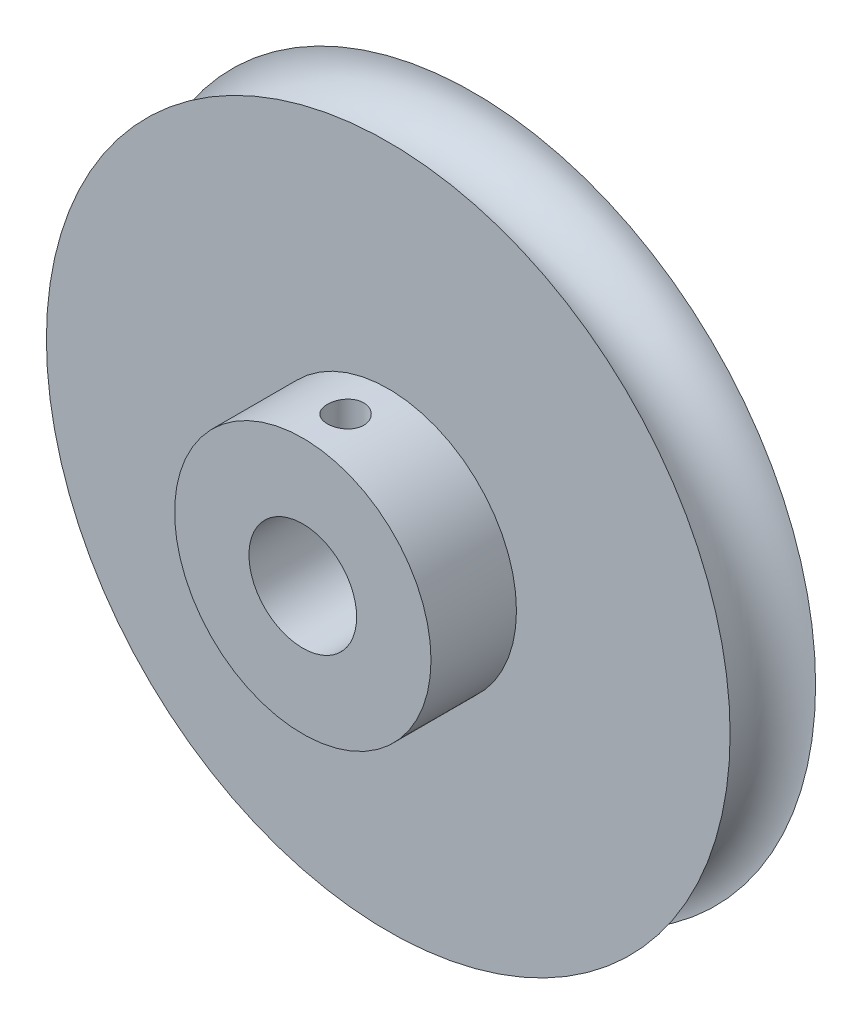
SolidWorks part; units mm, degrees
ref_plane "Front Plane" through (0, 0, 0) normal (0, 0, 1) x (1, 0, 0)
ref_plane "Top Plane" through (0, 0, 0) normal (0, 1, 0) x (1, 0, 0)
ref_plane "Right Plane" through (0, 0, 0) normal (1, 0, 0) x (0, 0, -1)
sketch "Sketch1" plane through (0, 0, 0) normal (0, 0, 1) x (1, 0, 0)
  circle A0 centre (0, 0) radius 25.4
extrude "Boss-Extrude1" add sketch "Sketch1" along normal blind 6.35
sketch "Sketch2" plane through (0, 0, 6.35) normal (0, 0, 1) x (1, 0, 0)
  circle A0 centre (0, 0) radius 9.525
extrude "Boss-Extrude2" add sketch "Sketch2" along normal blind 6.35
sketch "Sketch3" plane through (0, 0, 12.7) normal (0, 0, 1) x (1, 0, 0)
  circle A0 centre (0, 0) radius 4
extrude "Cut-Extrude1" cut sketch "Sketch3" against normal blind 12.7
sketch "Sketch4" plane through (0, 0, 0) normal (0, 1, 0) x (1, 0, 0)
  line L0 (25.4, -6.35) -> (25.4, 0)
  line L1 (0, 6.4243) -> (0, -16.8969) construction
  arc A0 (25.4, 0) -> (25.4, -6.35) centre (25.4, -3.175) ccw
revolve "Cut-Revolve1" cut sketch "Sketch4" angle 360 about L1
sketch "Sketch5" plane through (0, 0, 0) normal (0, 1, 0) x (1, 0, 0)
  circle A0 centre (0, -9.525) radius 1.8986
hole_wizard "#6-32 Tapped Hole1" positions "3DSketch1" profile "Sketch6" tap size "#6-32" standard "Ansi Inch"
sketch3d "3DSketch1"
  point P22 (0, 9.525, 9.525)
cosmetic thread "Hole Thread1" parameters "D1"=5.7606, "D2"=3.5052
sketch "Sketch6" plane through (0, 9.525, 9.525) normal (1, 0, 0) x (0, 0, 1)
  line L0 (0, 0) -> (0, 10.3367)
  line L1 (0, 10.3367) -> (1.3525, 9.524)
  line L2 (1.3525, 9.524) -> (1.3525, 0)
  line L5 (1.3525, 0) -> (0, 0)
  line L10 (0, 10.3367) -> (-1.3526, 9.524) construction
  line L11 (0, -6.35) -> (0, 107.95) construction
  dimension "Tap Drill Dia." = 2.7051
  dimension "Tap Drill Depth" = 9.524
  dimension "Drill Angle" = 118
